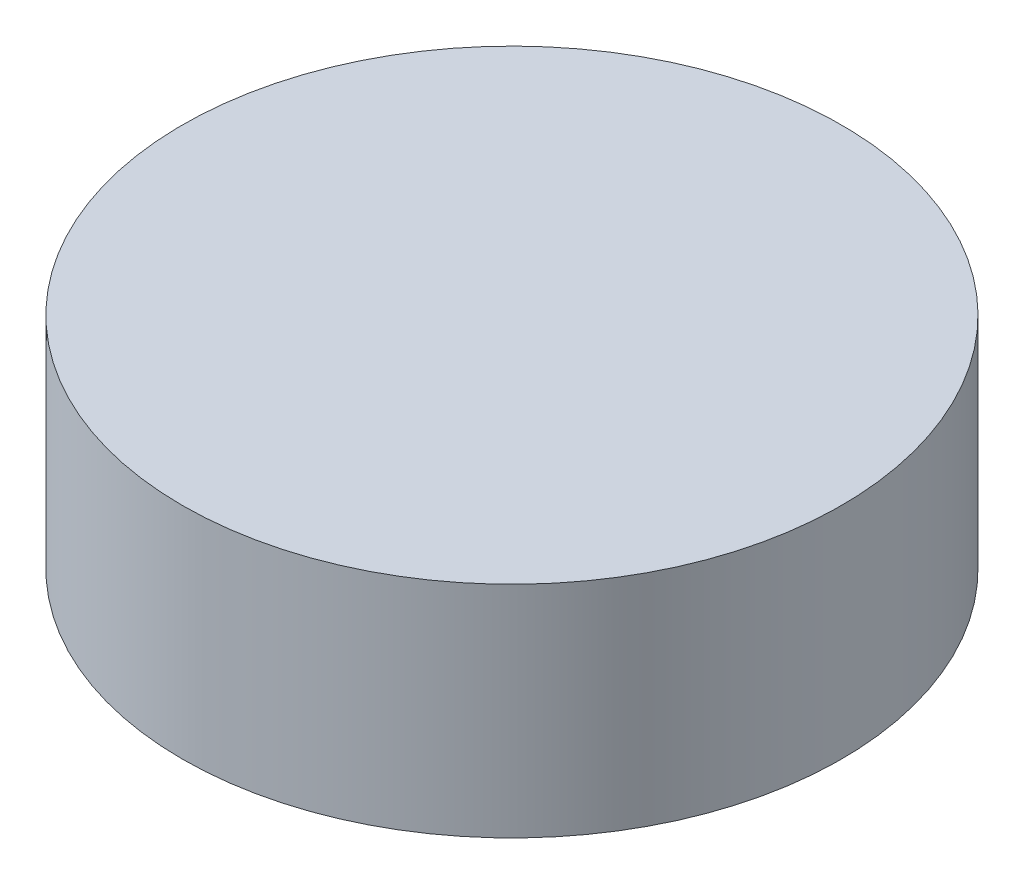
SolidWorks part; units mm, degrees
ref_plane "Plano frontal" through (0, 0, 0) normal (0, 0, 1) x (1, 0, 0)
ref_plane "Plano superior" through (0, 0, 0) normal (0, 1, 0) x (1, 0, 0)
ref_plane "Plano direito" through (0, 0, 0) normal (1, 0, 0) x (0, 0, -1)
sketch "Esboço1" plane through (0, 0, 0) normal (0, 1, 0) x (1, 0, 0)
  circle A0 centre (0, 0) radius 30
  dimension "D1" = 60
extrude "Ressalto-extrusão1" add sketch "Esboço1" along normal blind 20
sketch "Esboço2" plane through (0, 20, 0) normal (0, 1, 0) x (1, 0, 0)
  line L0 (0, 30) -> (0, 0)
  circle A0 centre (0, 0) radius 30 construction
sketch "Esboço3" plane through (0, 0, 0) normal (0, -1, 0) x (1, 0, 0)
  line L0 (-30, 0) -> (0, 0)
  line L1 (0, 0) -> (30, 0)
  circle A0 centre (0, 0) radius 30 construction
